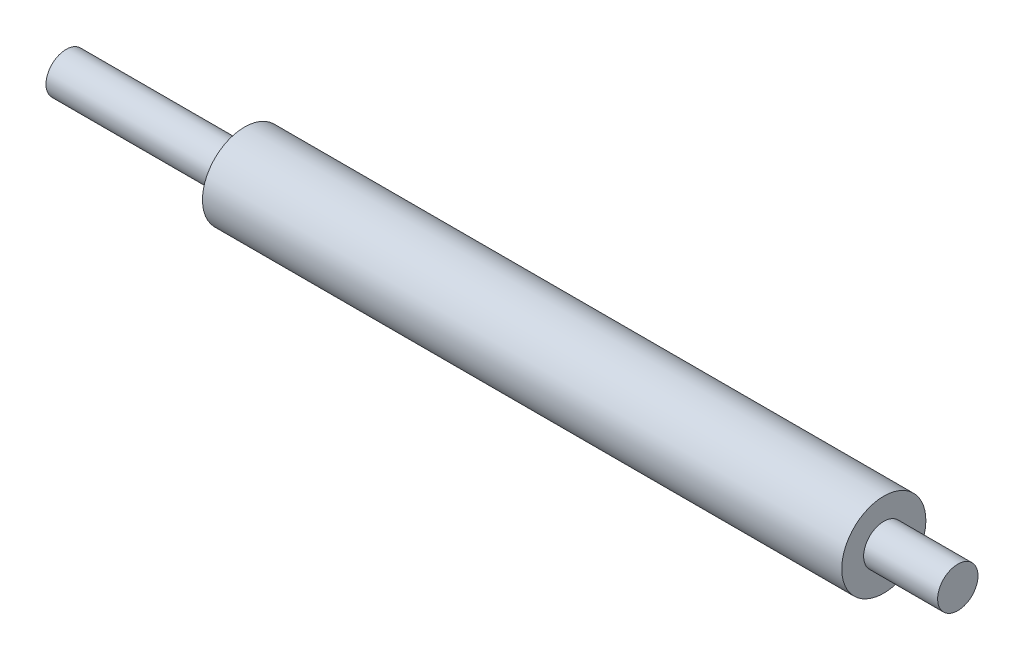
SolidWorks part; units mm, degrees
ref_plane "Front Plane" through (0, 0, 0) normal (0, 0, 1) x (1, 0, 0)
ref_plane "Top Plane" through (0, 0, 0) normal (0, 1, 0) x (1, 0, 0)
ref_plane "Right Plane" through (0, 0, 0) normal (1, 0, 0) x (0, 0, -1)
sketch "Sketch2" plane through (0, 0, 0) normal (0, 0, 1) x (1, 0, 0)
  line L0 (0, 0) -> (0, 6)
  line L1 (0, 6) -> (53, 6)
  line L2 (53, 6) -> (53, 12.5)
  line L3 (53, 12.5) -> (243, 12.5)
  line L4 (243, 12.5) -> (243, 6)
  line L5 (243, 6) -> (265, 6)
  line L6 (265, 6) -> (265, 0)
  line L7 (265, 0) -> (0, 0)
  dimension "D1" = 6
  dimension "D2" = 53
  dimension "D3" = 22
  dimension "D4" = 190
  dimension "D5" = 12.5
revolve "Revolve1" add sketch "Sketch2" angle 360 about L7
